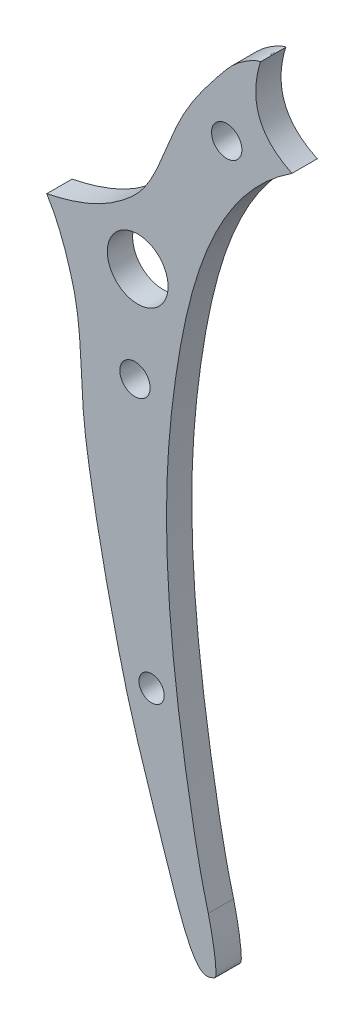
SolidWorks part; units mm, degrees
ref_plane "Front Plane" through (0, 0, 0) normal (0, 0, 1) x (1, 0, 0)
ref_plane "Top Plane" through (0, 0, 0) normal (0, 1, 0) x (1, 0, 0)
ref_plane "Right Plane" through (0, 0, 0) normal (1, 0, 0) x (0, 0, -1)
sketch "Sketch1" plane through (0, 0, 0) normal (0, 0, 1) x (1, 0, 0)
  line L0 (0, 0) -> (90.6353, 249.0185)
  line L1 (0, 0) -> (0, -15)
  line L2 (0, 0) -> (20.9373, -479.5431)
  circle A0 centre (90.6353, 249.0185) radius 15
  circle A1 centre (0, 0) radius 15
  circle A2 centre (16.4287, -256.271) radius 12.5
  circle A3 centre (2.7084, 95.5204) radius 30
  spline S0 degree 3 poles (155.1172, 253.5669) (80.9613, 205.0502) (44.4459, 80.1172) (23.7402, -128.7238) (44.7012, -287.6416) (65.3097, -394.1024) (72.4498, -420.8115) knots 0 0 0 0 0.356858 0.509383 0.894987 1 1 1 1
  spline S1 degree 2 poles (155.1172, 253.5669) (106.3933, 276.5901) (123.9915, 333.4118) knots 0 0 0 1 1 1
  spline S2 degree 3 poles (123.9915, 333.4118) (121.941, 333.9246) (103.1267, 325.5945) (76.8434, 293.7354) (36.5616, 242.8245) (21.3704, 176.1357) (-25.7972, 134.3601) (-52.7841, 122.3986) (-87.1862, 115.0279) knots 0 0 0 0 0.175011 0.215542 0.405319 0.676609 0.736077 1 1 1 1
  spline S3 degree 3 poles (-87.1862, 115.0279) (-76.5425, 98.2817) (-67.4879, 73.4004) (-52.089, 17.0397) (-54.2194, -35.9923) (-41.4171, -126.6761) (-11.0756, -267.5088) (3.32, -312.5762) (60.0249, -482.3385) (72.1572, -475.4013) (81.9098, -471.8922) (77.4792, -441.4881) (72.4498, -420.8115) knots 0 0 0 0 0.079931 0.106477 0.247802 0.285952 0.470307 0.743153 0.791096 0.932109 0.954762 1 1 1 1
  dimension "D4" = 30
  dimension "D5" = 30
  dimension "D2" = 60
  dimension "D8" = 25
  dimension "D1" = 265
  dimension "D3" = 160
  dimension "D6" = 2.5
extrude "Boss-Extrude1" add sketch "Sketch1" along normal blind 25
